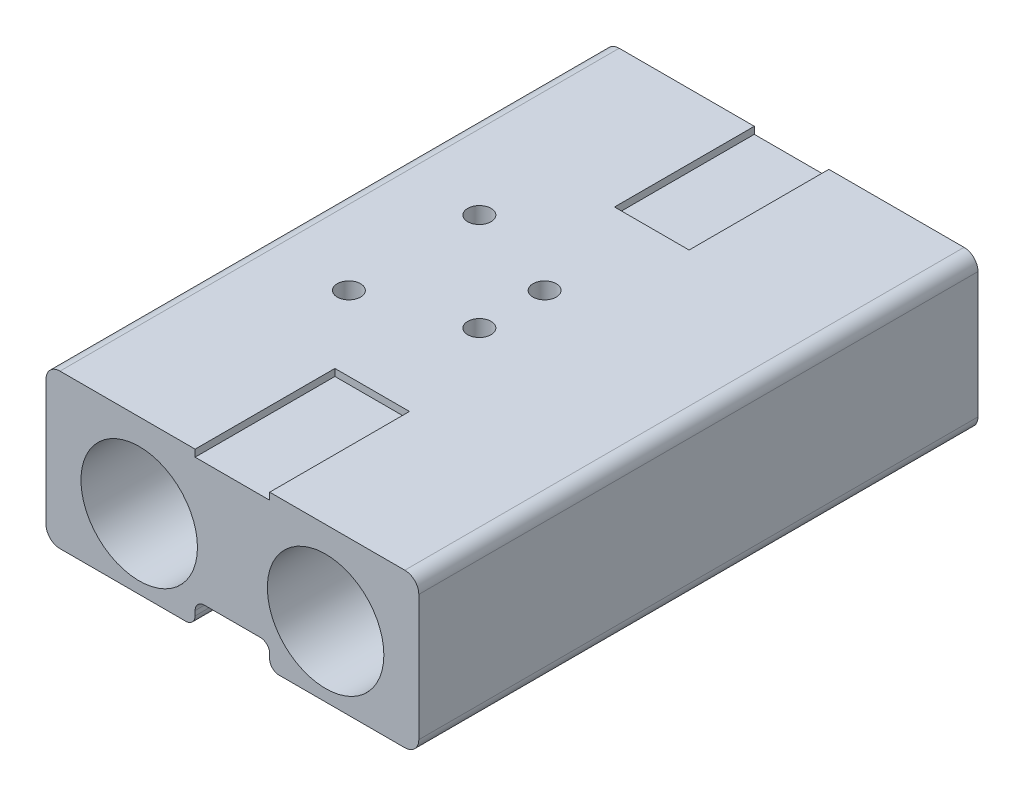
SolidWorks part; units mm, degrees
ref_plane "前视基准面" through (0, 0, 0) normal (0, 0, 1) x (1, 0, 0)
ref_plane "上视基准面" through (0, 0, 0) normal (0, 1, 0) x (1, 0, 0)
ref_plane "右视基准面" through (0, 0, 0) normal (1, 0, 0) x (0, 0, -1)
sketch "草图1" plane through (0, 0, 0) normal (0, 0, 1) x (1, 0, 0)
  line L2 (-20, -7.5) -> (-20, 9)
  line L3 (-20, 9) -> (20, 9)
  line L4 (20, -7.5) -> (20, 9)
  line L7 (0, -7.5) -> (-20, -7.5)
  line L8 (0, -7.5) -> (20, -7.5)
  circle A0 centre (-10, 0) radius 3.5
  circle A2 centre (10, 0) radius 3.5
  point P0 (0, 0)
extrude "凸台-拉伸1" add sketch "草图1" along normal blind 60
fillet "圆角1" radius 1.5 4 edges at (-20, 9, 30) (20, 9, 30) (20, -7.5, 30) (-20, -7.5, 30)
sketch "草图2" plane through (0, 0, 60) normal (0, 0, 1) x (1, 0, 0)
  circle A0 centre (10, 0) radius 6.25
  circle A1 centre (-10, 0) radius 6.25
extrude "切除-拉伸1" cut sketch "草图2" against normal blind 20
sketch "草图3" plane through (0, 0, 0) normal (0, 0, -1) x (-1, 0, 0)
  circle A0 centre (-10, 0) radius 6.25
  circle A1 centre (10, 0) radius 6.25
extrude "切除-拉伸2" cut sketch "草图3" against normal blind 20
sketch "草图5" plane through (0, 0, 0) normal (0, 0, -1) x (-1, 0, 0)
  line L7 (0, -5) -> (4, -5)
  line L8 (4, -5) -> (4, -9)
  line L9 (4, -9) -> (-4, -9)
  line L10 (-4, -9) -> (-4, -5)
  line L11 (-4, -5) -> (0, -5)
  line L12 (-4, 8.25) -> (4, 8.25)
  line L13 (4, 8.25) -> (4, 9)
  line L14 (18.5, 9) -> (-18.5, 9) construction
  line L15 (4, 9) -> (-4, 9)
  line L16 (-4, 9) -> (-4, 8.25)
extrude "切除-拉伸4" cut sketch "草图5" against normal blind 62
fillet "圆角2" radius 1 4 edges at (-4, -5, 30) (4, -5, 30) (-4, -7.5, 30) (4, -7.5, 30)
sketch "草图7" plane through (0, 9, 0) normal (0, 1, 0) x (1, 0, 0)
  line L0 (-4, -60) -> (-4, 0) construction
  line L10 (4, -15) -> (-4, -15)
  line L11 (4, -15) -> (4, -45)
  line L12 (4, -45) -> (-4, -45)
  line L13 (-4, -15) -> (-4, -45)
extrude "凸台-拉伸2" add sketch "草图7" against normal blind 2
sketch "草图6" plane through (0, 9, 0) normal (0, 1, 0) x (1, 0, 0)
  circle A0 centre (0, -26.5) radius 1.25
  circle A1 centre (0, -33.5) radius 1.25
extrude "切除-拉伸5" cut sketch "草图6" against normal blind 62
sketch "草图8" plane through (0, 9, 0) normal (0, 1, 0) x (1, 0, 0)
  circle A0 centre (-10.5, -23) radius 1.25
  circle A1 centre (-10.5, -37) radius 1.25
extrude "切除-拉伸6" cut sketch "草图8" against normal blind 5
sketch "草图9" plane through (0, -5, 0) normal (0, -1, 0) x (1, 0, 0)
  line L1 (2.4749, 28.9749) -> (2.4749, 31.0251)
  line L3 (-2.4749, 28.9749) -> (-2.4749, 31.0251)
  arc A0 (2.4749, 31.0251) -> (-2.4749, 31.0251) centre (0, 33.5) ccw
  arc A1 (-2.4749, 28.9749) -> (2.4749, 28.9749) centre (0, 26.5) ccw
extrude "切除-拉伸9" cut sketch "草图9" against normal blind 8 and the other way blind 5
